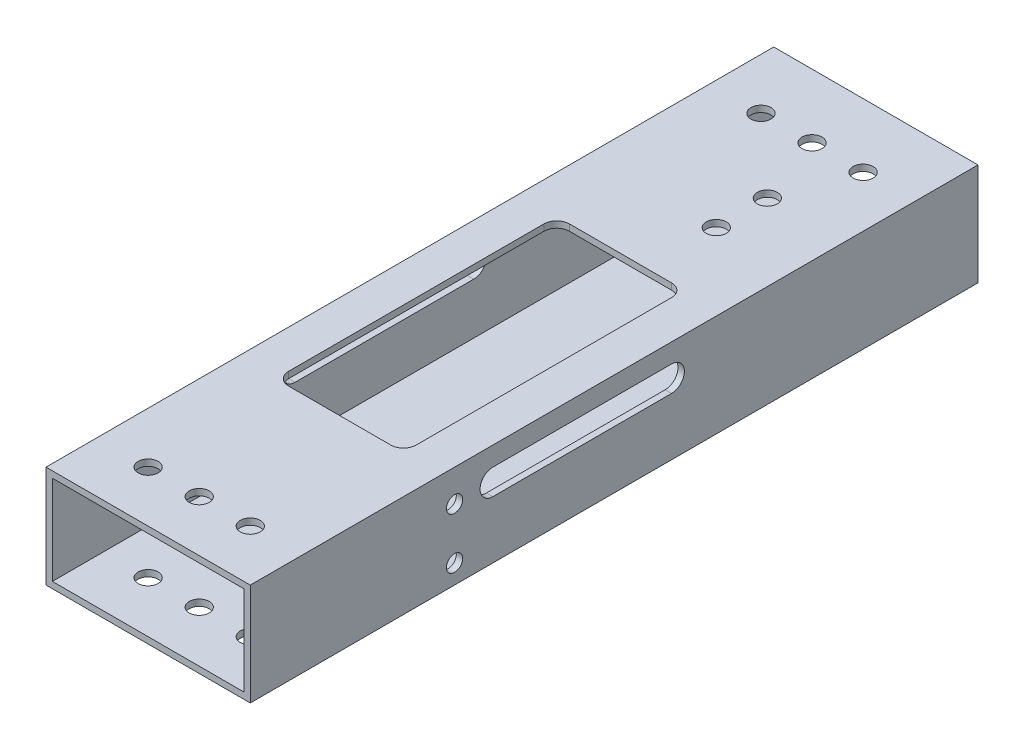
SolidWorks part; units mm, degrees
other "Markup4"
sketch "Sketch7" plane through (25.4, -12.7, 0) normal (0.9921, -0.1226, -0.0275) x (-0.1217, -0.992, 0.0335)
other "Markup5"
sketch "Sketch10"
material "6061-T6 (SS)"
ref_plane "Front Plane" through (0, 0, 0) normal (0, 0, 1) x (1, 0, 0)
ref_plane "Top Plane" through (0, 0, 0) normal (0, 1, 0) x (1, 0, 0)
ref_plane "Right Plane" through (0, 0, 0) normal (1, 0, 0) x (0, 0, -1)
sketch "Sketch1" plane through (0, 0, 0) normal (0, 0, 1) x (1, 0, 0)
  line L1 (-25.4, -12.7) -> (25.4, -12.7)
  line L2 (-25.4, -12.7) -> (-25.4, 12.7)
  line L3 (-25.4, 12.7) -> (25.4, 12.7)
  line L4 (25.4, -12.7) -> (25.4, 12.7)
  line L5 (-25.4, -12.7) -> (25.4, 12.7) construction
  line L6 (-25.4, 12.7) -> (25.4, -12.7) construction
  line L7 (-23.8125, -11.1125) -> (23.8125, -11.1125)
  line L8 (-23.8125, -11.1125) -> (-23.8125, 11.1125)
  line L9 (-23.8125, 11.1125) -> (23.8125, 11.1125)
  line L10 (23.8125, -11.1125) -> (23.8125, 11.1125)
  line L11 (-23.8125, -11.1125) -> (23.8125, 11.1125) construction
  line L12 (-23.8125, 11.1125) -> (23.8125, -11.1125) construction
  point P0 (0, 0)
  point P6 (0, 0)
  dimension "D1" = 50.8
  dimension "D2" = 25.4
  dimension "D3" = 1.5875
  dimension "D4" = 1.5875
extrude "Boss-Extrude1" add sketch "Sketch1" along normal blind 180.975
sketch "Sketch2" plane through (0, 12.7, 0) normal (0, 1, 0) x (1, 0, 0)
  line L0 (25.4, 0) -> (-25.4, 0) construction
  line L1 (-25.4, -180.975) -> (-25.4, 0) construction
  line L3 (25.4, -180.975) -> (-25.4, -180.975) construction
  circle A0 centre (-12.7, -15.875) radius 2.4892
  circle A1 centre (0, -15.875) radius 2.4892
  circle A2 centre (12.7, -15.875) radius 2.4892
  circle A3 centre (-12.7, -168.275) radius 2.4892
  circle A4 centre (0, -168.275) radius 2.4892
  circle A5 centre (12.7, -168.275) radius 2.4892
  circle A6 centre (6.35, -33.3375) radius 2.4892
  circle A7 centre (6.35, -46.0375) radius 2.4892
  dimension "D1" = 4.9784
  dimension "D2" = 15.875
  dimension "D3" = 12.7
  dimension "D4" = 12.7
  dimension "D5" = 12.7
  dimension "D6" = 12.7
  dimension "D7" = 31.75
  dimension "D8" = 33.3375
extrude "Cut-Extrude1" cut sketch "Sketch2" against normal through all
sketch "Sketch9" plane through (0, 12.7, 0) normal (0, 1, 0) x (1, 0, 0)
  line L0 (25.4, 0) -> (-25.4, 0) construction
  line L1 (-15.875, -63.5) -> (15.875, -63.5)
  line L2 (-15.875, -63.5) -> (-15.875, -133.35)
  line L3 (-15.875, -133.35) -> (15.875, -133.35)
  line L4 (15.875, -63.5) -> (15.875, -133.35)
  line L5 (-25.4, -180.975) -> (-25.4, 0) construction
  dimension "D1" = 63.5
  dimension "D2" = 31.75
  dimension "D3" = 9.525
  dimension "D4" = 69.85
extrude "Cut-Extrude2" cut sketch "Sketch9" against normal up to surface (23.8125 mm away) up to face at (0, -11.1125, 18.3642)
fillet "Fillet1" radius 3.175 4 edges at (-15.875, 11.9062, 63.5) (15.875, 11.9062, 133.35) (-15.875, 11.9062, 133.35) (15.875, 11.9062, 63.5)
sketch "Sketch11" plane through (0, 0, 0) normal (1, 0, 0) x (0, 0, -1)
  line L0 (-120.65, 4.7625) -> (-76.2, 4.7625) construction
  line L1 (-120.65, 7.9375) -> (-76.2, 7.9375)
  line L2 (-120.65, 1.5875) -> (-76.2, 1.5875)
  line L3 (-130.175, 12.7) -> (-66.675, 12.7) construction
  line L4 (-180.975, 12.7) -> (0, 12.7) construction
  arc A0 (-120.65, 7.9375) -> (-120.65, 1.5875) centre (-120.65, 4.7625) ccw
  arc A1 (-76.2, 1.5875) -> (-76.2, 7.9375) centre (-76.2, 4.7625) ccw
  circle A2 centre (-130.175, 4.7625) radius 2.0193
  circle A3 centre (-130.175, -7.9375) radius 2.0193
  circle A4 centre (-98.425, 4.7625) radius 9.525 construction
  point P2 (-98.425, 4.7625)
  point P10 (-98.425, 12.7)
  point P12 (-127.1438, 7.9375)
  point P17 (-128.125, 4.7625)
  point P18 (-127.5101, -7.4843)
  point P19 (0, 0)
  dimension "D1" = 3.175
  dimension "D4" = 4.0386
  dimension "D6" = 19.05
  dimension "D2" = 44.45
  dimension "D3" = 7.9375
  dimension "D5" = 9.525
  dimension "D7" = 12.7
extrude "Cut-Extrude3" cut sketch "Sketch11" against normal through all both and the other way through all
